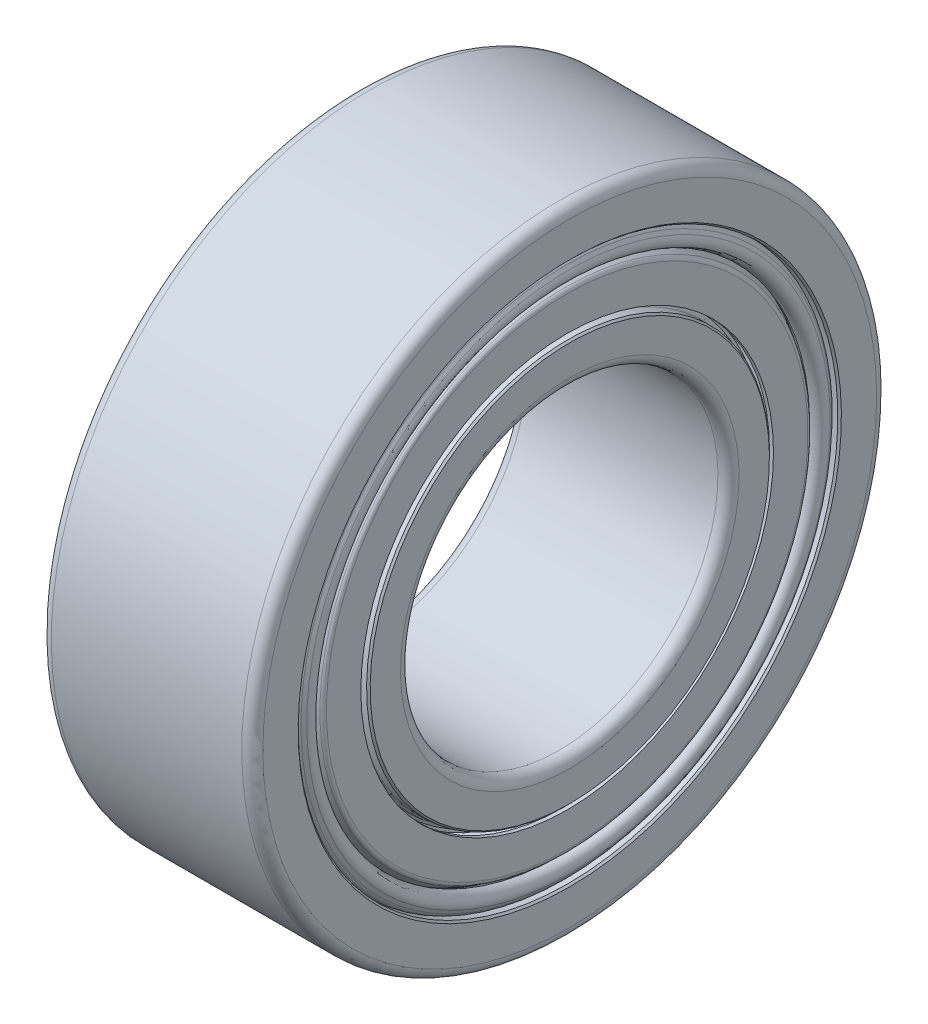
SolidWorks part; units mm, degrees
ref_plane "Front Plane" through (0, 0, 0) normal (0, 0, 1) x (1, 0, 0)
ref_plane "Top Plane" through (0, 0, 0) normal (0, 1, 0) x (1, 0, 0)
ref_plane "Right Plane" through (0, 0, 0) normal (1, 0, 0) x (0, 0, -1)
sketch "Sketch1" plane through (0, 0, 0) normal (1, 0, 0) x (0, 0, -1)
  line L0 (0, 6) -> (0, 5.8) construction
  line L1 (0, 3) -> (0, 3.2) construction
  circle A0 centre (0, 0) radius 6
  circle A1 centre (0, 0) radius 3
  circle A2 centre (0, 0) radius 5.1 construction
  circle A3 centre (0, 0) radius 3.9 construction
  dimension "OD" = 12
  dimension "ID" = 6
  dimension "Outer Ring ID" = 10.2
  dimension "Inner Ring OD" = 7.8
  dimension "Radius" = 0.2
sketch "Sketch2" plane through (0, 0, 0) normal (0, 0, 1) x (1, 0, 0)
  line L0 (-2, 6) -> (2, 6) construction
  point P3 (0, 6)
  dimension "Width" = 4
sketch "Sketch3" plane through (0, 0, 0) normal (0, 0, 1) x (1, 0, 0)
  line L0 (-1.8, 6) -> (1.8, 6)
  line L1 (-2, 5.8) -> (-2, 5.1337)
  line L2 (2, 5.8) -> (2, 5.1337)
  line L3 (-1.9662, 5.1) -> (-1.7, 5.1)
  line L4 (-1.9662, 3.8072) -> (-2, 3.7734)
  line L5 (-1.7891, 3.8072) -> (-1.9662, 3.8072)
  line L6 (2, 5.1337) -> (1.9662, 5.1)
  line L7 (0, 6) -> (0, 5.1) construction
  line L8 (-2, 5.1337) -> (-1.9662, 5.1)
  line L9 (1.9662, 3.8072) -> (1.9662, 3.9) construction
  line L10 (-1.6625, 3.9) -> (-1.6625, 3.954)
  line L11 (-1.8, 3) -> (1.8, 3)
  line L12 (-2, 3.2) -> (-2, 3.7734)
  line L13 (2, 3.2) -> (2, 3.7734)
  line L14 (-1.6625, 3.9) -> (1.6625, 3.9) construction
  line L15 (1.6625, 3.9) -> (1.6625, 3.6667) construction
  line L16 (1.6625, 3.6667) -> (1.6625, 3.4333) construction
  line L17 (1.6625, 3.9) -> (1.6625, 3.8072) construction
  line L18 (1.6625, 3.8072) -> (1.9662, 3.8072) construction
  line L19 (1.9662, 3.8072) -> (2, 3.7734)
  line L20 (1.7891, 3.8072) -> (1.9662, 3.8072)
  line L21 (1.6625, 3.4333) -> (1.6625, 3.2) construction
  line L22 (-1.8, 0) -> (1.8, 0) construction
  line L23 (1.7, 5.1) -> (1.7, 5.154)
  line L24 (1.7, 5.154) -> (-1.7, 5.154)
  line L25 (-1.7, 5.1) -> (-1.7, 5.154)
  line L26 (1.7, 5.1) -> (1.9662, 5.1)
  line L27 (-1.6625, 3.954) -> (1.6625, 3.954)
  line L28 (1.6625, 3.954) -> (1.6625, 3.9)
  arc A0 (-2, 5.8) -> (-1.8, 6) centre (-1.8, 5.8) cw
  arc A1 (1.8, 6) -> (2, 5.8) centre (1.8, 5.8) cw
  arc A2 (-2, 3.2) -> (-1.8, 3) centre (-1.8, 3.2) ccw
  arc A3 (1.8, 3) -> (2, 3.2) centre (1.8, 3.2) ccw
  arc A4 (1.6625, 3.9) -> (1.7891, 3.8072) centre (1.7891, 3.9399) ccw
  arc A5 (-1.6625, 3.9) -> (-1.7891, 3.8072) centre (-1.7891, 3.9399) cw
  point P7 (-2, 6)
  point P15 (2, 6)
  point P30 (0, 3.9)
  point P48 (0, 5.154)
  dimension "D1" = 0.2
  dimension "D4" = 0.2
  dimension "D2" = 135
  dimension "D3" = 0.0338
  dimension "D5" = 135
  dimension "D7" = 0.3375
  dimension "D9" = 0.054
  dimension "D10" = 0.3
  dimension "D8" = 0.1266
  dimension "D6" = 0.1266
revolve "Revolve1" add sketch "Sketch3" angle 360 about L22
sketch "Sketch4" plane through (0, 0, 0) normal (0, 0, 1) x (1, 0, 0)
  line L6 (1.7883, 4.7878) -> (1.7533, 4.808) construction
  line L7 (1.7033, 4.935) -> (1.7033, 4.756)
  line L8 (1.7133, 4.7387) -> (1.905, 4.628)
  line L9 (1.95, 4.5501) -> (1.95, 3.9)
  line L10 (2, -5.8) -> (2, 5.8) construction
  line L11 (1.95, 3.9) -> (1.87, 3.9) construction
  line L12 (1.9233, 4.8657) -> (1.95, 4.8657) construction
  line L15 (1.7533, 4.808) -> (1.7133, 4.7387) construction
  line L18 (1.8713, 4.98) -> (1.9113, 4.9107)
  line L20 (1.7, 5.1) -> (1.9662, 5.1) construction
  arc A0 (1.7033, 4.935) -> (1.8713, 4.98) centre (1.7933, 4.935) cw
  arc A1 (1.9113, 4.9107) -> (1.7883, 4.7878) centre (1.8333, 4.8657) cw construction
  arc A2 (1.905, 4.628) -> (1.95, 4.5501) centre (1.86, 4.5501) cw
  arc A3 (1.7033, 4.756) -> (1.7133, 4.7387) centre (1.7233, 4.756) ccw
  arc A4 (1.9113, 4.9107) -> (1.8333, 4.7757) centre (1.8333, 4.8657) cw
  point P18 (1.6625, 3.9)
  point P28 (1.95, 4.6021)
  point P31 (1.7033, 4.7445)
  dimension "D8" = 0.09
  dimension "D9" = 0.02
  dimension "D6" = 0.09
  dimension "D1" = 0.05
  dimension "D2" = 0.08
  dimension "D7" = 30
  dimension "D4" = 120
  dimension "D12" = 0.0267
  dimension "D5" = 0.075
revolve "Revolve-Thin1" add sketch "Sketch4" angle 360 about L22
mirror "Mirror2" about plane through (0, 0, 0) normal (1, 0, 0) of bodies 106
delete or keep bodies "Body-Delete/Keep 1" type delete bodies bodies 113
mirror "Mirror1" about plane through (0, 0, 0) normal (1, 0, 0) of bodies 106 112
equation "\"D4@Sketch3\"=\"D1@Sketch3\""
equation "\"D1@Sketch3\"=\"Radius@Sketch1\""
equation "\"D8@Sketch4\"=\"D3@Sketch4\"*1.125"
equation "\"D9@Sketch4\"=\"D3@Sketch4\"*.25"
equation "\"Outer Ring ID@Sketch1\"=\"OD@Sketch1\"-(((\"OD@Sketch1\"-\"ID@Sketch1\")/2)*.3*2)"
equation "\"Inner Ring OD@Sketch1\"=\"ID@Sketch1\"+(((\"OD@Sketch1\"-\"ID@Sketch1\")/2)*.3*2)"
equation "\"Radius@Sketch1\"=\"Width@Sketch2\"*.05"
equation "\"D3@Sketch4\"=\"Width@Sketch2\"*.02"
equation "\"D2@Sketch4\"=\"D3@Sketch4\""
equation "\"D12@Sketch4\"=\"D3@Sketch4\"/3"
equation "\"D6@Sketch4\"=((\"Outer Ring ID@Sketch1\"-\"Inner Ring OD@Sketch1\")/2)*.075"
equation "\"D10@Sketch3\"=\"Width@Sketch2\"*.075"
equation "\"D9@Sketch3\"=((\"OD@Sketch1\"-\"Outer Ring ID@Sketch1\")/2)*.06"
equation "\"D3@Sketch3\"=\"D9@Sketch3\"*.625"
equation "\"D7@Sketch3\"=\"D10@Sketch3\"*1.125"
equation "\"D6@Sketch3\"=\"D7@Sketch3\"*.375"
equation "\"D8@Sketch3\"=\"D6@Sketch3\""
equation "\"D1@Sketch4\"=\"D3@Sketch4\"*.625"
equation "\"D5@Sketch4\"=((\"Outer Ring ID@Sketch1\"-\"Inner Ring OD@Sketch1\")/2)*.0625"
equation "\"D3@Revolve-Thin1\"=\"D5@Sketch4\""
